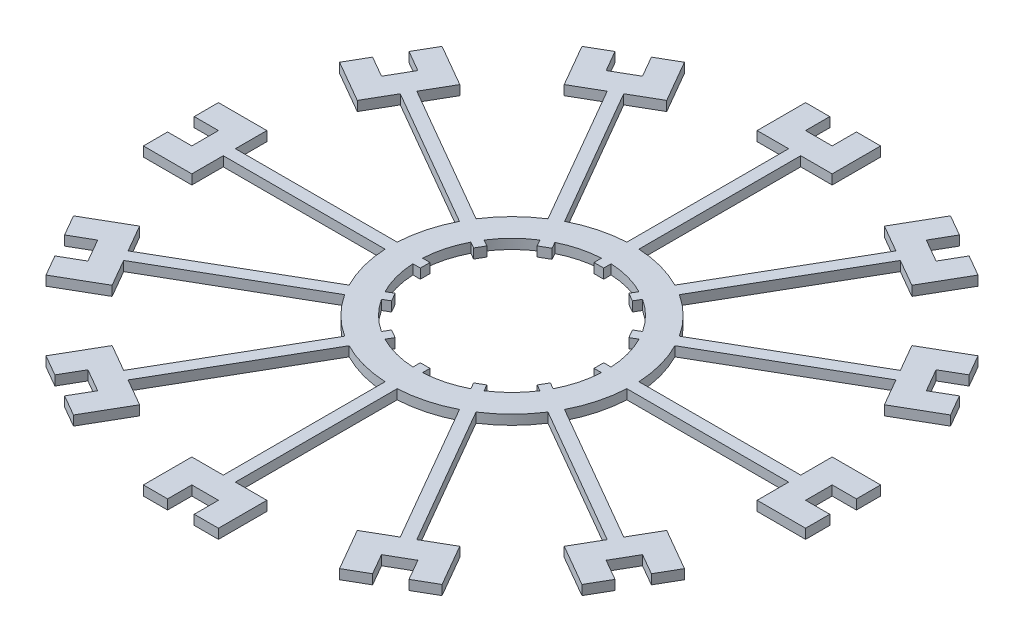
SolidWorks part; units mm, degrees
ref_plane "Front Plane" through (0, 0, 0) normal (0, 0, 1) x (1, 0, 0)
ref_plane "Top Plane" through (0, 0, 0) normal (0, 1, 0) x (1, 0, 0)
ref_plane "Right Plane" through (0, 0, 0) normal (1, 0, 0) x (0, 0, -1)
sketch "Sketch1" plane through (0, 0, 0) normal (0, 1, 0) x (1, 0, 0)
  line L12 (-1.25, -17.69) -> (1.25, -17.69)
  line L189 (-1.25, -17.69) -> (-1.25, -19.2094)
  line L191 (-1.25, -58.39) -> (-7.75, -58.39)
  line L192 (-7.75, -58.39) -> (-7.75, -68.39)
  line L193 (-7.75, -68.39) -> (-2.75, -68.39)
  line L195 (-2.75, -68.39) -> (-2.75, -63.39)
  line L196 (-2.75, -63.39) -> (2.75, -63.39)
  line L197 (7.75, -68.39) -> (2.75, -68.39)
  line L198 (2.75, -68.39) -> (2.75, -63.39)
  line L199 (1.25, -17.69) -> (1.25, -19.25)
  line L200 (1.25, -58.39) -> (7.75, -58.39)
  line L201 (7.75, -58.39) -> (7.75, -68.39)
  line L202 (0, 27.3373) -> (0, -27.3373) construction
  line L203 (1.25, -19.25) -> (4.1738, -19.25) construction
  line L204 (-9.9275, -14.695) -> (-7.7625, -15.945)
  line L205 (-7.7625, -15.945) -> (-8.5222, -17.2608)
  line L206 (-28.1125, -51.1922) -> (-22.4833, -54.4422)
  line L207 (-22.4833, -54.4422) -> (-27.4833, -63.1025)
  line L208 (-27.4833, -63.1025) -> (-31.8134, -60.6025)
  line L209 (-31.8134, -60.6025) -> (-29.3134, -56.2724)
  line L210 (-34.0766, -53.5224) -> (-29.3134, -56.2724)
  line L211 (-36.5766, -57.8525) -> (-34.0766, -53.5224)
  line L212 (-40.9067, -55.3525) -> (-36.5766, -57.8525)
  line L213 (-35.9067, -46.6922) -> (-40.9067, -55.3525)
  line L214 (-30.2775, -49.9422) -> (-35.9067, -46.6922)
  line L215 (-9.9275, -14.695) -> (-10.6872, -16.0108)
  line L216 (-15.945, -7.7625) -> (-14.695, -9.9275)
  line L217 (-14.695, -9.9275) -> (-16.0108, -10.6872)
  line L218 (-49.9422, -30.2775) -> (-46.6922, -35.9067)
  line L219 (-46.6922, -35.9067) -> (-55.3525, -40.9067)
  line L220 (-55.3525, -40.9067) -> (-57.8525, -36.5766)
  line L221 (-57.8525, -36.5766) -> (-53.5224, -34.0766)
  line L222 (-56.2724, -29.3134) -> (-53.5224, -34.0766)
  line L223 (-60.6025, -31.8134) -> (-56.2724, -29.3134)
  line L224 (-63.1025, -27.4833) -> (-60.6025, -31.8134)
  line L225 (-54.4422, -22.4833) -> (-63.1025, -27.4833)
  line L226 (-51.1922, -28.1125) -> (-54.4422, -22.4833)
  line L227 (-15.945, -7.7625) -> (-17.2608, -8.5222)
  line L228 (-17.69, 1.25) -> (-17.69, -1.25)
  line L229 (-17.69, -1.25) -> (-19.2094, -1.25)
  line L230 (-58.39, -1.25) -> (-58.39, -7.75)
  line L231 (-58.39, -7.75) -> (-68.39, -7.75)
  line L232 (-68.39, -7.75) -> (-68.39, -2.75)
  line L233 (-68.39, -2.75) -> (-63.39, -2.75)
  line L234 (-63.39, 2.75) -> (-63.39, -2.75)
  line L235 (-68.39, 2.75) -> (-63.39, 2.75)
  line L236 (-68.39, 7.75) -> (-68.39, 2.75)
  line L237 (-58.39, 7.75) -> (-68.39, 7.75)
  line L238 (-58.39, 1.25) -> (-58.39, 7.75)
  line L239 (-17.69, 1.25) -> (-19.2094, 1.25)
  line L242 (-51.1922, 28.1125) -> (-54.4422, 22.4833)
  line L243 (-54.4422, 22.4833) -> (-63.1025, 27.4833)
  line L244 (-63.1025, 27.4833) -> (-60.6025, 31.8134)
  line L245 (-60.6025, 31.8134) -> (-56.2724, 29.3134)
  line L246 (-53.5224, 34.0766) -> (-56.2724, 29.3134)
  line L247 (-57.8525, 36.5766) -> (-53.5224, 34.0766)
  line L248 (-55.3525, 40.9067) -> (-57.8525, 36.5766)
  line L249 (-46.6922, 35.9067) -> (-55.3525, 40.9067)
  line L250 (-49.9422, 30.2775) -> (-46.6922, 35.9067)
  line L252 (-7.546, 16.07) -> (-9.9275, 14.695)
  line L253 (-9.9275, 14.695) -> (-10.6872, 16.0108)
  line L254 (-30.2775, 49.9422) -> (-35.9067, 46.6922)
  line L255 (-35.9067, 46.6922) -> (-40.9067, 55.3525)
  line L256 (-40.9067, 55.3525) -> (-36.5766, 57.8525)
  line L257 (-36.5766, 57.8525) -> (-34.0766, 53.5224)
  line L258 (-29.3134, 56.2724) -> (-34.0766, 53.5224)
  line L259 (-31.8134, 60.6025) -> (-29.3134, 56.2724)
  line L260 (-27.4833, 63.1025) -> (-31.8134, 60.6025)
  line L261 (-22.4833, 54.4422) -> (-27.4833, 63.1025)
  line L262 (-28.1125, 51.1922) -> (-22.4833, 54.4422)
  line L264 (1.25, 17.69) -> (-1.25, 17.69)
  line L265 (-1.25, 17.69) -> (-1.25, 19.2094)
  line L266 (-1.25, 58.39) -> (-7.75, 58.39)
  line L267 (-7.75, 58.39) -> (-7.75, 68.39)
  line L268 (-7.75, 68.39) -> (-2.75, 68.39)
  line L269 (-2.75, 68.39) -> (-2.75, 63.39)
  line L270 (2.75, 63.39) -> (-2.75, 63.39)
  line L271 (2.75, 68.39) -> (2.75, 63.39)
  line L272 (7.75, 68.39) -> (2.75, 68.39)
  line L273 (7.75, 58.39) -> (7.75, 68.39)
  line L274 (1.25, 58.39) -> (7.75, 58.39)
  line L275 (1.25, 17.69) -> (1.25, 19.2094)
  line L276 (9.9275, 14.695) -> (7.7625, 15.945)
  line L277 (7.7625, 15.945) -> (8.5222, 17.2608)
  line L278 (28.1125, 51.1922) -> (22.4833, 54.4422)
  line L279 (22.4833, 54.4422) -> (27.4833, 63.1025)
  line L280 (27.4833, 63.1025) -> (31.8134, 60.6025)
  line L281 (31.8134, 60.6025) -> (29.3134, 56.2724)
  line L282 (34.0766, 53.5224) -> (29.3134, 56.2724)
  line L283 (36.5766, 57.8525) -> (34.0766, 53.5224)
  line L284 (40.9067, 55.3525) -> (36.5766, 57.8525)
  line L285 (35.9067, 46.6922) -> (40.9067, 55.3525)
  line L286 (30.2775, 49.9422) -> (35.9067, 46.6922)
  line L287 (9.9275, 14.695) -> (10.6872, 16.0108)
  line L288 (0, 0) -> (51.5882, -51.5882) construction
  line L289 (15.945, 7.7625) -> (14.695, 9.9275)
  line L290 (14.695, 9.9275) -> (16.0108, 10.6872)
  line L291 (49.9422, 30.2775) -> (46.6922, 35.9067)
  line L292 (46.6922, 35.9067) -> (55.3525, 40.9067)
  line L293 (55.3525, 40.9067) -> (57.8525, 36.5766)
  line L294 (57.8525, 36.5766) -> (53.5224, 34.0766)
  line L295 (56.2724, 29.3134) -> (53.5224, 34.0766)
  line L296 (60.6025, 31.8134) -> (56.2724, 29.3134)
  line L297 (63.1025, 27.4833) -> (60.6025, 31.8134)
  line L298 (54.4422, 22.4833) -> (63.1025, 27.4833)
  line L299 (51.1922, 28.1125) -> (54.4422, 22.4833)
  line L300 (15.945, 7.7625) -> (17.2608, 8.5222)
  line L301 (17.69, -1.25) -> (17.69, 1.25)
  line L302 (17.69, 1.25) -> (19.2094, 1.25)
  line L303 (58.39, 1.25) -> (58.39, 7.75)
  line L304 (58.39, 7.75) -> (68.39, 7.75)
  line L305 (68.39, 7.75) -> (68.39, 2.75)
  line L306 (68.39, 2.75) -> (63.39, 2.75)
  line L307 (63.39, -2.75) -> (63.39, 2.75)
  line L308 (68.39, -2.75) -> (63.39, -2.75)
  line L309 (68.39, -7.75) -> (68.39, -2.75)
  line L310 (58.39, -7.75) -> (68.39, -7.75)
  line L311 (58.39, -1.25) -> (58.39, -7.75)
  line L312 (17.69, -1.25) -> (19.2094, -1.25)
  line L313 (14.695, -9.9275) -> (15.945, -7.7625)
  line L314 (15.945, -7.7625) -> (17.2608, -8.5222)
  line L315 (51.1922, -28.1125) -> (54.4422, -22.4833)
  line L316 (54.4422, -22.4833) -> (63.1025, -27.4833)
  line L317 (63.1025, -27.4833) -> (60.6025, -31.8134)
  line L318 (60.6025, -31.8134) -> (56.2724, -29.3134)
  line L319 (53.5224, -34.0766) -> (56.2724, -29.3134)
  line L320 (57.8525, -36.5766) -> (53.5224, -34.0766)
  line L321 (55.3525, -40.9067) -> (57.8525, -36.5766)
  line L322 (46.6922, -35.9067) -> (55.3525, -40.9067)
  line L323 (49.9422, -30.2775) -> (46.6922, -35.9067)
  line L324 (14.695, -9.9275) -> (16.0108, -10.6872)
  line L325 (7.7625, -15.945) -> (9.9275, -14.695)
  line L326 (9.9275, -14.695) -> (10.6872, -16.0108)
  line L327 (30.2775, -49.9422) -> (35.9067, -46.6922)
  line L328 (35.9067, -46.6922) -> (40.9067, -55.3525)
  line L329 (40.9067, -55.3525) -> (36.5766, -57.8525)
  line L330 (36.5766, -57.8525) -> (34.0766, -53.5224)
  line L331 (29.3134, -56.2724) -> (34.0766, -53.5224)
  line L332 (31.8134, -60.6025) -> (29.3134, -56.2724)
  line L333 (27.4833, -63.1025) -> (31.8134, -60.6025)
  line L334 (22.4833, -54.4422) -> (27.4833, -63.1025)
  line L335 (28.1125, -51.1922) -> (22.4833, -54.4422)
  line L336 (7.7625, -15.945) -> (8.5222, -17.2608)
  line L337 (-8.5222, -17.2608) -> (-11.4018, -22.2486) construction
  line L338 (-11.4018, -22.2486) -> (-28.1125, -51.1922)
  line L339 (-10.6872, -16.0108) -> (-13.5669, -20.9986) construction
  line L340 (-13.5669, -20.9986) -> (-30.2775, -49.9422)
  line L341 (-16.0108, -10.6872) -> (-20.9986, -13.5669) construction
  line L342 (-20.9986, -13.5669) -> (-49.9422, -30.2775)
  line L343 (-17.2608, -8.5222) -> (-22.2486, -11.4018) construction
  line L344 (-22.2486, -11.4018) -> (-51.1922, -28.1125)
  line L345 (-19.2094, -1.25) -> (-24.9687, -1.25) construction
  line L346 (-24.9687, -1.25) -> (-58.39, -1.25)
  line L347 (-19.2094, 1.25) -> (-24.9687, 1.25) construction
  line L348 (-24.9687, 1.25) -> (-58.39, 1.25)
  line L349 (-17.2608, 8.5222) -> (-22.2486, 11.4018) construction
  line L350 (-22.2486, 11.4018) -> (-51.1922, 28.1125)
  line L351 (-16.0108, 10.6872) -> (-20.9986, 13.5669) construction
  line L352 (-20.9986, 13.5669) -> (-49.9422, 30.2775)
  line L353 (-10.6872, 16.0108) -> (-13.5669, 20.9986) construction
  line L354 (-13.5669, 20.9986) -> (-30.2775, 49.9422)
  line L355 (0, 0) -> (-36.1266, 20.8577) construction
  line L356 (-11.3872, 22.256) -> (-28.1125, 51.1922)
  line L357 (1.25, 19.2094) -> (1.25, 24.9687) construction
  line L358 (1.25, 24.9687) -> (1.25, 58.39)
  line L359 (-1.25, 19.2094) -> (-1.25, 24.9687) construction
  line L360 (-1.25, 24.9687) -> (-1.25, 58.39)
  line L361 (8.5222, 17.2608) -> (11.4018, 22.2486) construction
  line L362 (11.4018, 22.2486) -> (28.1125, 51.1922)
  line L363 (10.6872, 16.0108) -> (13.5669, 20.9986) construction
  line L364 (13.5669, 20.9986) -> (30.2775, 49.9422)
  line L365 (16.0108, 10.6872) -> (20.9986, 13.5669) construction
  line L366 (20.9986, 13.5669) -> (49.9422, 30.2775)
  line L367 (17.2608, 8.5222) -> (22.2486, 11.4018) construction
  line L368 (22.2486, 11.4018) -> (51.1922, 28.1125)
  line L369 (19.2094, 1.25) -> (24.9687, 1.25) construction
  line L370 (24.9687, 1.25) -> (58.39, 1.25)
  line L371 (19.2094, -1.25) -> (24.9687, -1.25) construction
  line L372 (24.9687, -1.25) -> (58.39, -1.25)
  line L373 (17.2608, -8.5222) -> (22.2486, -11.4018) construction
  line L374 (22.2486, -11.4018) -> (51.1922, -28.1125)
  line L375 (16.0108, -10.6872) -> (20.9986, -13.5669) construction
  line L376 (20.9986, -13.5669) -> (49.9422, -30.2775)
  line L377 (10.6872, -16.0108) -> (13.5669, -20.9986) construction
  line L378 (13.5669, -20.9986) -> (30.2775, -49.9422)
  line L379 (8.5222, -17.2608) -> (11.4018, -22.2486) construction
  line L380 (11.4018, -22.2486) -> (28.1125, -51.1922)
  line L381 (1.25, -19.25) -> (1.25, -24.9687) construction
  line L382 (1.25, -24.9687) -> (1.25, -58.39)
  line L383 (-1.25, -19.2094) -> (-1.25, -24.9687) construction
  line L384 (-1.25, -24.9687) -> (-1.25, -58.39)
  line L385 (0, 0) -> (9.5064, -16.4656) construction
  line L386 (0, 0) -> (17.0094, -9.8204) construction
  line L387 (-7.8732, 16.1697) -> (-9.836, 15.0365)
  line L388 (-9.836, 15.0365) -> (-10.6032, 16.3653)
  line L389 (-15.0365, 9.836) -> (-16.3653, 10.6032)
  line L390 (-15.0365, 9.836) -> (-16.0365, 8.104)
  line L391 (-16.0365, 8.104) -> (-17.3653, 8.8711)
  line L392 (-17.94, 1) -> (-19.4743, 1)
  line L393 (-17.94, 1) -> (-17.94, -1)
  line L394 (-17.94, -1) -> (-19.4743, -1)
  line L395 (-16.0365, -8.104) -> (-17.3653, -8.8711)
  line L396 (-16.0365, -8.104) -> (-15.0365, -9.836)
  line L397 (-15.0365, -9.836) -> (-16.3653, -10.6032)
  line L398 (-9.836, -15.0365) -> (-10.6032, -16.3653)
  line L399 (-9.836, -15.0365) -> (-8.104, -16.0365)
  line L400 (-8.104, -16.0365) -> (-8.8711, -17.3653)
  line L401 (-1, -17.94) -> (-1, -19.4743)
  line L402 (-1, -17.94) -> (1, -17.94)
  line L403 (1, -17.94) -> (1, -19.4743)
  line L404 (11.3037, -22.5785) -> (27.771, -51.1007)
  line L405 (27.771, -51.1007) -> (22.1418, -54.3507)
  line L406 (22.1418, -54.3507) -> (27.3918, -63.444)
  line L407 (27.3918, -63.444) -> (32.1549, -60.694)
  line L408 (32.1549, -60.694) -> (29.6549, -56.3639)
  line L409 (29.6549, -56.3639) -> (33.9851, -53.8639)
  line L410 (36.4851, -58.194) -> (33.9851, -53.8639)
  line L411 (41.2482, -55.444) -> (36.4851, -58.194)
  line L412 (35.9982, -46.3507) -> (41.2482, -55.444)
  line L413 (30.369, -49.6007) -> (35.9982, -46.3507)
  line L414 (13.9017, -21.0785) -> (30.369, -49.6007)
  line L415 (21.0785, -13.9017) -> (49.6007, -30.369)
  line L416 (49.6007, -30.369) -> (46.3507, -35.9982)
  line L417 (46.3507, -35.9982) -> (55.444, -41.2482)
  line L418 (55.444, -41.2482) -> (58.194, -36.4851)
  line L419 (58.194, -36.4851) -> (53.8639, -33.9851)
  line L420 (53.8639, -33.9851) -> (56.3639, -29.6549)
  line L421 (60.694, -32.1549) -> (56.3639, -29.6549)
  line L422 (63.444, -27.3918) -> (60.694, -32.1549)
  line L423 (54.3507, -22.1418) -> (63.444, -27.3918)
  line L424 (51.1007, -27.771) -> (54.3507, -22.1418)
  line L425 (22.5785, -11.3037) -> (51.1007, -27.771)
  line L426 (25.2054, -1.5) -> (58.14, -1.5)
  line L427 (58.14, -1.5) -> (58.14, -8)
  line L428 (58.14, -8) -> (68.64, -8)
  line L429 (68.64, -8) -> (68.64, -2.5)
  line L430 (68.64, -2.5) -> (63.64, -2.5)
  line L431 (63.64, -2.5) -> (63.64, 2.5)
  line L432 (68.64, 2.5) -> (63.64, 2.5)
  line L433 (68.64, 8) -> (68.64, 2.5)
  line L434 (58.14, 8) -> (68.64, 8)
  line L435 (58.14, 1.5) -> (58.14, 8)
  line L436 (25.2054, 1.5) -> (58.14, 1.5)
  line L437 (22.5785, 11.3037) -> (51.1007, 27.771)
  line L438 (51.1007, 27.771) -> (54.3507, 22.1418)
  line L439 (54.3507, 22.1418) -> (63.444, 27.3918)
  line L440 (63.444, 27.3918) -> (60.694, 32.1549)
  line L441 (60.694, 32.1549) -> (56.3639, 29.6549)
  line L442 (56.3639, 29.6549) -> (53.8639, 33.9851)
  line L443 (58.194, 36.4851) -> (53.8639, 33.9851)
  line L444 (55.444, 41.2482) -> (58.194, 36.4851)
  line L445 (46.3507, 35.9982) -> (55.444, 41.2482)
  line L446 (49.6007, 30.369) -> (46.3507, 35.9982)
  line L447 (21.0785, 13.9017) -> (49.6007, 30.369)
  line L448 (13.9017, 21.0785) -> (30.369, 49.6007)
  line L449 (30.369, 49.6007) -> (35.9982, 46.3507)
  line L450 (35.9982, 46.3507) -> (41.2482, 55.444)
  line L451 (41.2482, 55.444) -> (36.4851, 58.194)
  line L452 (36.4851, 58.194) -> (33.9851, 53.8639)
  line L453 (33.9851, 53.8639) -> (29.6549, 56.3639)
  line L454 (32.1549, 60.694) -> (29.6549, 56.3639)
  line L455 (27.3918, 63.444) -> (32.1549, 60.694)
  line L456 (22.1418, 54.3507) -> (27.3918, 63.444)
  line L457 (27.771, 51.1007) -> (22.1418, 54.3507)
  line L458 (11.3037, 22.5785) -> (27.771, 51.1007)
  line L459 (1.5, 25.2054) -> (1.5, 58.14)
  line L460 (1.5, 58.14) -> (8, 58.14)
  line L461 (8, 58.14) -> (8, 68.64)
  line L462 (8, 68.64) -> (2.5, 68.64)
  line L463 (2.5, 68.64) -> (2.5, 63.64)
  line L464 (2.5, 63.64) -> (-2.5, 63.64)
  line L465 (-2.5, 68.64) -> (-2.5, 63.64)
  line L466 (-8, 68.64) -> (-2.5, 68.64)
  line L467 (-8, 58.14) -> (-8, 68.64)
  line L468 (-1.5, 58.14) -> (-8, 58.14)
  line L469 (-1.5, 25.2054) -> (-1.5, 58.14)
  line L470 (-11.2891, 22.5858) -> (-27.7709, 51.1008)
  line L471 (-27.7709, 51.1008) -> (-22.1418, 54.3507)
  line L472 (-22.1418, 54.3507) -> (-27.3918, 63.444)
  line L473 (-27.3918, 63.444) -> (-32.1549, 60.694)
  line L474 (-32.1549, 60.694) -> (-29.6549, 56.3639)
  line L475 (-29.6549, 56.3639) -> (-33.9851, 53.8639)
  line L476 (-36.4851, 58.194) -> (-33.9851, 53.8639)
  line L477 (-41.2482, 55.444) -> (-36.4851, 58.194)
  line L478 (-35.9982, 46.3507) -> (-41.2482, 55.444)
  line L479 (-30.369, 49.6007) -> (-35.9982, 46.3507)
  line L480 (-13.9017, 21.0785) -> (-30.369, 49.6007)
  line L481 (-21.0785, 13.9017) -> (-49.6007, 30.369)
  line L482 (-49.6007, 30.369) -> (-46.3507, 35.9982)
  line L483 (-46.3507, 35.9982) -> (-55.444, 41.2482)
  line L484 (-55.444, 41.2482) -> (-58.194, 36.4851)
  line L485 (-58.194, 36.4851) -> (-53.8639, 33.9851)
  line L486 (-53.8639, 33.9851) -> (-56.3639, 29.6549)
  line L487 (-60.694, 32.1549) -> (-56.3639, 29.6549)
  line L488 (-63.444, 27.3918) -> (-60.694, 32.1549)
  line L489 (-54.3507, 22.1418) -> (-63.444, 27.3918)
  line L490 (-51.1007, 27.771) -> (-54.3507, 22.1418)
  line L491 (-22.5785, 11.3037) -> (-51.1007, 27.771)
  line L492 (-25.2054, 1.5) -> (-58.14, 1.5)
  line L493 (-58.14, 1.5) -> (-58.14, 8)
  line L494 (-58.14, 8) -> (-68.64, 8)
  line L495 (-68.64, 8) -> (-68.64, 2.5)
  line L496 (-68.64, 2.5) -> (-63.64, 2.5)
  line L497 (-63.64, 2.5) -> (-63.64, -2.5)
  line L498 (-68.64, -2.5) -> (-63.64, -2.5)
  line L499 (-68.64, -8) -> (-68.64, -2.5)
  line L500 (-58.14, -8) -> (-68.64, -8)
  line L501 (-58.14, -1.5) -> (-58.14, -8)
  line L502 (-25.2054, -1.5) -> (-58.14, -1.5)
  line L503 (-22.5785, -11.3037) -> (-51.1007, -27.771)
  line L504 (-51.1007, -27.771) -> (-54.3507, -22.1418)
  line L505 (-54.3507, -22.1418) -> (-63.444, -27.3918)
  line L506 (-63.444, -27.3918) -> (-60.694, -32.1549)
  line L507 (-60.694, -32.1549) -> (-56.3639, -29.6549)
  line L508 (-56.3639, -29.6549) -> (-53.8639, -33.9851)
  line L509 (-58.194, -36.4851) -> (-53.8639, -33.9851)
  line L510 (-55.444, -41.2482) -> (-58.194, -36.4851)
  line L511 (-46.3507, -35.9982) -> (-55.444, -41.2482)
  line L512 (-49.6007, -30.369) -> (-46.3507, -35.9982)
  line L513 (-21.0785, -13.9017) -> (-49.6007, -30.369)
  line L514 (-13.9017, -21.0785) -> (-30.369, -49.6007)
  line L515 (-30.369, -49.6007) -> (-35.9982, -46.3507)
  line L516 (-35.9982, -46.3507) -> (-41.2482, -55.444)
  line L517 (-41.2482, -55.444) -> (-36.4851, -58.194)
  line L518 (-36.4851, -58.194) -> (-33.9851, -53.8639)
  line L519 (-33.9851, -53.8639) -> (-29.6549, -56.3639)
  line L520 (-32.1549, -60.694) -> (-29.6549, -56.3639)
  line L521 (-27.3918, -63.444) -> (-32.1549, -60.694)
  line L522 (-22.1418, -54.3507) -> (-27.3918, -63.444)
  line L523 (-27.771, -51.1007) -> (-22.1418, -54.3507)
  line L524 (-11.3037, -22.5785) -> (-27.771, -51.1007)
  line L525 (-1.5, -25.2054) -> (-1.5, -58.14)
  line L526 (-1.5, -58.14) -> (-8, -58.14)
  line L527 (-8, -58.14) -> (-8, -68.64)
  line L528 (-8, -68.64) -> (-2.5, -68.64)
  line L529 (-2.5, -68.64) -> (-2.5, -63.64)
  line L530 (-2.5, -63.64) -> (2.5, -63.64)
  line L531 (2.5, -68.64) -> (2.5, -63.64)
  line L532 (8, -68.64) -> (2.5, -68.64)
  line L533 (8, -58.14) -> (8, -68.64)
  line L534 (1.5, -58.14) -> (8, -58.14)
  line L535 (1.5, -25.2054) -> (1.5, -58.14)
  line L536 (8.104, -16.0365) -> (8.8711, -17.3653)
  line L537 (8.104, -16.0365) -> (9.836, -15.0365)
  line L538 (9.836, -15.0365) -> (10.6032, -16.3653)
  line L539 (15.0365, -9.836) -> (16.3653, -10.6032)
  line L540 (15.0365, -9.836) -> (16.0365, -8.104)
  line L541 (16.0365, -8.104) -> (17.3653, -8.8711)
  line L542 (17.94, -1) -> (19.4743, -1)
  line L543 (17.94, -1) -> (17.94, 1)
  line L544 (17.94, 1) -> (19.4743, 1)
  line L545 (16.0365, 8.104) -> (17.3653, 8.8711)
  line L546 (16.0365, 8.104) -> (15.0365, 9.836)
  line L547 (15.0365, 9.836) -> (16.3653, 10.6032)
  line L548 (9.836, 15.0365) -> (10.6032, 16.3653)
  line L549 (9.836, 15.0365) -> (8.104, 16.0365)
  line L550 (8.104, 16.0365) -> (8.8711, 17.3653)
  line L551 (1, 17.94) -> (1, 19.4743)
  line L552 (1, 17.94) -> (-1, 17.94)
  line L553 (-1, 17.94) -> (-1, 19.4743)
  line L554 (1, -17.94) -> (1, -19.25) construction
  line L555 (-7.546, 16.07) -> (-8.2967, 17.3703)
  line L556 (-7.7482, 15.9532) -> (-9.9275, 14.695) construction
  line L557 (-7.7625, 15.945) -> (-7.8875, 16.1615) [skipped]
  line L558 (-7.8732, 16.1697) -> (-8.6327, 17.4851)
  line L559 (-7.8732, 16.1697) -> (-8.6327, 17.4851)
  line L561 (-14.695, 9.9275) -> (-15.945, 7.7625) [skipped]
  line L562 (-14.695, 9.9275) -> (-15.945, 7.7625) construction
  line L563 (-14.695, 9.9275) -> (-16.0108, 10.6872) [skipped]
  line L564 (-14.695, 9.9275) -> (-16.0108, 10.6872) construction
  line L565 (-15.945, 7.7625) -> (-17.2608, 8.5222) [skipped]
  line L566 (-15.945, 7.7625) -> (-17.2608, 8.5222) construction
  arc A0 (-1.25, 19.2094) -> (-8.2967, 17.3703) centre (0, 0) ccw construction
  arc A1 (-20.9986, -13.5669) -> (-13.5669, -20.9986) centre (0, 0) ccw
  arc A2 (-1.25, 19.2094) -> (-8.2967, 17.3703) centre (0, 0) ccw
  arc A3 (-10.6872, 16.0108) -> (-16.0108, 10.6872) centre (0, 0) ccw construction
  arc A5 (-17.2608, 8.5222) -> (-19.2094, 1.25) centre (0, 0) ccw construction
  arc A7 (-19.2094, -1.25) -> (-17.2608, -8.5222) centre (0, 0) ccw construction
  arc A8 (-19.2094, -1.25) -> (-17.2608, -8.5222) centre (0, 0) ccw
  arc A9 (-16.0108, -10.6872) -> (-10.6872, -16.0108) centre (0, 0) ccw construction
  arc A10 (-16.0108, -10.6872) -> (-10.6872, -16.0108) centre (0, 0) ccw
  arc A11 (-8.5222, -17.2608) -> (-1.25, -19.2094) centre (0, 0) ccw construction
  arc A12 (-8.5222, -17.2608) -> (-1.25, -19.2094) centre (0, 0) ccw
  arc A13 (1.25, -19.2094) -> (8.5222, -17.2608) centre (0, 0) ccw construction
  arc A14 (1.25, -19.2094) -> (8.5222, -17.2608) centre (0, 0) ccw
  arc A15 (10.6872, -16.0108) -> (16.0108, -10.6872) centre (0, 0) ccw construction
  arc A16 (10.6872, -16.0108) -> (16.0108, -10.6872) centre (0, 0) ccw
  arc A17 (17.2608, -8.5222) -> (19.2094, -1.25) centre (0, 0) ccw construction
  arc A18 (17.2608, -8.5222) -> (19.2094, -1.25) centre (0, 0) ccw
  arc A19 (19.2094, 1.25) -> (17.2608, 8.5222) centre (0, 0) ccw construction
  arc A20 (19.2094, 1.25) -> (17.2608, 8.5222) centre (0, 0) ccw
  arc A21 (16.0108, 10.6872) -> (10.6872, 16.0108) centre (0, 0) ccw construction
  arc A22 (16.0108, 10.6872) -> (10.6872, 16.0108) centre (0, 0) ccw
  arc A23 (8.5222, 17.2608) -> (1.25, 19.2094) centre (0, 0) ccw construction
  arc A24 (8.5222, 17.2608) -> (1.25, 19.2094) centre (0, 0) ccw
  arc A25 (-22.2486, -11.4018) -> (-20.9986, -13.5669) centre (0, 0) ccw construction
  arc A26 (-13.5669, -20.9986) -> (-11.4018, -22.2486) centre (0, 0) ccw construction
  arc A27 (-11.4018, -22.2486) -> (-1.25, -24.9687) centre (0, 0) ccw
  arc A28 (-24.9687, 1.25) -> (-24.9687, -1.25) centre (0, 0) ccw construction
  arc A29 (-24.9687, -1.25) -> (-22.2486, -11.4018) centre (0, 0) ccw
  arc A30 (-20.9986, 13.5669) -> (-22.2486, 11.4018) centre (0, 0) ccw construction
  arc A31 (-22.2486, 11.4018) -> (-24.9687, 1.25) centre (0, 0) ccw
  arc A32 (-11.3872, 22.256) -> (-13.5669, 20.9986) centre (0, 0) ccw construction
  arc A33 (-13.5669, 20.9986) -> (-20.9986, 13.5669) centre (0, 0) ccw
  arc A34 (0, 25) -> (-1.25, 24.9687) centre (0, 0) ccw construction
  arc A35 (-1.25, 24.9687) -> (-11.3872, 22.256) centre (0, 0) ccw
  arc A36 (1.25, 24.9687) -> (0, 25) centre (0, 0) ccw construction
  arc A37 (13.5669, 20.9986) -> (11.4018, 22.2486) centre (0, 0) ccw construction
  arc A38 (11.4018, 22.2486) -> (1.25, 24.9687) centre (0, 0) ccw
  arc A39 (22.2486, 11.4018) -> (20.9986, 13.5669) centre (0, 0) ccw construction
  arc A40 (20.9986, 13.5669) -> (13.5669, 20.9986) centre (0, 0) ccw
  arc A41 (24.9687, -1.25) -> (24.9687, 1.25) centre (0, 0) ccw construction
  arc A42 (24.9687, 1.25) -> (22.2486, 11.4018) centre (0, 0) ccw
  arc A43 (20.9986, -13.5669) -> (22.2486, -11.4018) centre (0, 0) ccw construction
  arc A44 (22.2486, -11.4018) -> (24.9687, -1.25) centre (0, 0) ccw
  arc A45 (11.4018, -22.2486) -> (13.5669, -20.9986) centre (0, 0) ccw construction
  arc A46 (13.5669, -20.9986) -> (20.9986, -13.5669) centre (0, 0) ccw
  arc A47 (-1.25, -24.9687) -> (0, -25) centre (0, 0) ccw construction
  arc A48 (1.25, -24.9687) -> (11.4018, -22.2486) centre (0, 0) ccw
  arc A49 (0, -25) -> (1.25, -24.9687) centre (0, 0) ccw construction
  arc A50 (-10.6032, 16.3653) -> (-16.3653, 10.6032) centre (0, 0) ccw
  arc A51 (-17.3653, 8.8711) -> (-19.4743, 1) centre (0, 0) ccw
  arc A52 (-19.4743, -1) -> (-17.3653, -8.8711) centre (0, 0) ccw
  arc A53 (-16.3653, -10.6032) -> (-10.6032, -16.3653) centre (0, 0) ccw
  arc A54 (-8.8711, -17.3653) -> (-1, -19.4743) centre (0, 0) ccw
  arc A55 (1.5, -25.2054) -> (11.3037, -22.5785) centre (0, 0) ccw
  arc A56 (13.9017, -21.0785) -> (21.0785, -13.9017) centre (0, 0) ccw
  arc A57 (22.5785, -11.3037) -> (25.2054, -1.5) centre (0, 0) ccw
  arc A58 (25.2054, 1.5) -> (22.5785, 11.3037) centre (0, 0) ccw
  arc A59 (21.0785, 13.9017) -> (13.9017, 21.0785) centre (0, 0) ccw
  arc A60 (11.3037, 22.5785) -> (1.5, 25.2054) centre (0, 0) ccw
  arc A61 (-1.5, 25.2054) -> (-11.2891, 22.5858) centre (0, 0) ccw
  arc A62 (-13.9017, 21.0785) -> (-21.0785, 13.9017) centre (0, 0) ccw
  arc A63 (-22.5785, 11.3037) -> (-25.2054, 1.5) centre (0, 0) ccw
  arc A64 (-25.2054, -1.5) -> (-22.5785, -11.3037) centre (0, 0) ccw
  arc A65 (-21.0785, -13.9017) -> (-13.9017, -21.0785) centre (0, 0) ccw
  arc A66 (-11.3037, -22.5785) -> (-1.5, -25.2054) centre (0, 0) ccw
  arc A67 (1, -19.4743) -> (8.8711, -17.3653) centre (0, 0) ccw
  arc A68 (10.6032, -16.3653) -> (16.3653, -10.6032) centre (0, 0) ccw
  arc A69 (17.3653, -8.8711) -> (19.4743, -1) centre (0, 0) ccw
  arc A70 (19.4743, 1) -> (17.3653, 8.8711) centre (0, 0) ccw
  arc A71 (16.3653, 10.6032) -> (10.6032, 16.3653) centre (0, 0) ccw
  arc A72 (8.8711, 17.3653) -> (1, 19.4743) centre (0, 0) ccw
  arc A73 (-1, 19.4743) -> (-8.6327, 17.4851) centre (0, 0) ccw
  arc A74 (1.2662, -19.4588) -> (8.8711, -17.3653) centre (0, 0) ccw construction
  arc A75 (-1.25, 19.2094) -> (-8.5049, 17.2693) centre (0, 0) ccw construction
  arc A76 (-1, 19.4743) -> (-8.6153, 17.4936) centre (0, 0) ccw construction
  arc A77 (-10.6872, 16.0108) -> (-16.0108, 10.6872) centre (0, 0) ccw construction
  arc A78 (-17.2608, 8.5222) -> (-19.2094, 1.25) centre (0, 0) ccw construction
  point P105 (0, 0)
  point P202 (8.845, -15.32)
  point P203 (15.32, -8.845)
  point P208 (-15.5365, 8.97)
  dimension "D5" = 10
  dimension "D8" = 1.56
  dimension "D9" = 45
  dimension "D10" = 12
  dimension "D13" = 30
  dimension "D7" = 0.25
  dimension "D11" = 50
  dimension "D12" = 38.5
  dimension "D1" = 2.5
  dimension "D2" = 45.7
  dimension "D3" = 15.5
  dimension "D4" = 5
  dimension "D6" = 5.5
extrude "Boss-Extrude1" add sketch "Sketch1" along normal mid plane 2 contours L382 A48 L380 L335 L334 L333 L332 L331 L330 L329 L328 L327 L378 A46 L376 L323 L322 L321 L320 L319 L318 L317 L316 L315 L374 A44 L372 L311 L310 L309 L308 L307 L306 L305 L304 L303 L370 A42 L368 L299 L298 L297 L296 L295 L294 L293 L292 L291 L366 A40 L364 | L218 L219 L220 L221 L222 L223 L224 L225 L226 L227 L216 L217
